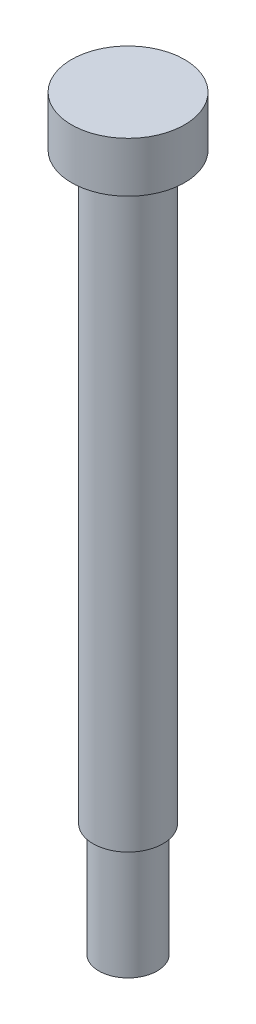
SolidWorks part; units mm, degrees
ref_plane "前视基准面" through (0, 0, 0) normal (0, 0, 1) x (1, 0, 0)
ref_plane "上视基准面" through (0, 0, 0) normal (0, 1, 0) x (1, 0, 0)
ref_plane "右视基准面" through (0, 0, 0) normal (1, 0, 0) x (0, 0, -1)
sketch "草图1" plane through (0, 0, 0) normal (0, 1, 0) x (1, 0, 0)
  circle A0 centre (0, 0) radius 4.85
  dimension "D1" = 9.7
extrude "凸台-拉伸1" add sketch "草图1" along normal blind 4.3
sketch "草图2" plane through (0, 0, 0) normal (0, -1, 0) x (1, 0, 0)
  circle A0 centre (0, 0) radius 3
  dimension "D1" = 6
extrude "凸台-拉伸2" add sketch "草图2" along normal blind 50
sketch "草图3" plane through (0, -50, 0) normal (0, -1, 0) x (1, 0, 0)
  circle A0 centre (0, 0) radius 2.5
  dimension "D1" = 5
extrude "凸台-拉伸3" add sketch "草图3" along normal blind 9.7
cosmetic thread "装饰螺纹线1" parameters "D2"=4
